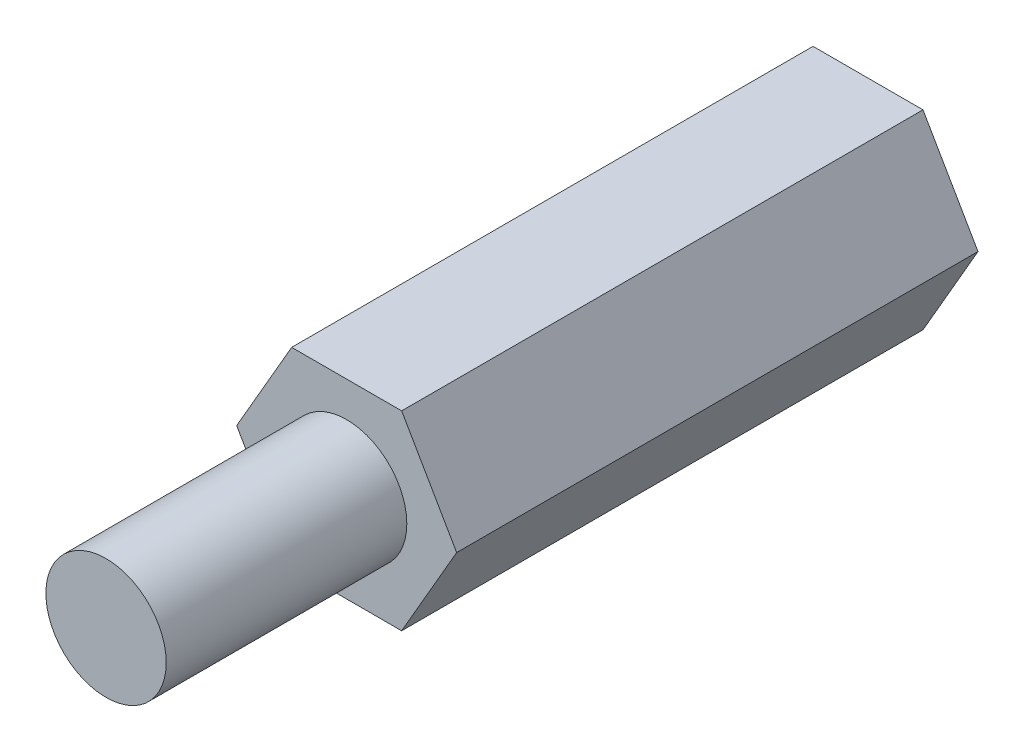
SolidWorks part; units mm, degrees
ref_plane "前视基准面" through (0, 0, 0) normal (0, 0, 1) x (1, 0, 0)
ref_plane "上视基准面" through (0, 0, 0) normal (0, 1, 0) x (1, 0, 0)
ref_plane "右视基准面" through (0, 0, 0) normal (1, 0, 0) x (0, 0, -1)
sketch "草图9" plane through (0, 0, 0) normal (0, 0, 1) x (1, 0, 0)
  line L1 (2.7424, 0) -> (1.3712, 2.375)
  line L2 (1.3712, 2.375) -> (-1.3712, 2.375)
  line L3 (-1.3712, 2.375) -> (-2.7424, 0)
  line L4 (-2.7424, 0) -> (-1.3712, -2.375)
  line L5 (-1.3712, -2.375) -> (1.3712, -2.375)
  line L6 (1.3712, -2.375) -> (2.7424, 0)
  circle A0 centre (0, 0) radius 2.375 construction
  dimension "D1" = 4.75
extrude "凸台-拉伸2" add sketch "草图9" along normal blind 13
sketch "草图10" plane through (0, 0, 13) normal (0, 0, 1) x (1, 0, 0)
  circle A0 centre (0, 0) radius 1.5
extrude "凸台-拉伸3" add sketch "草图10" along normal blind 6
